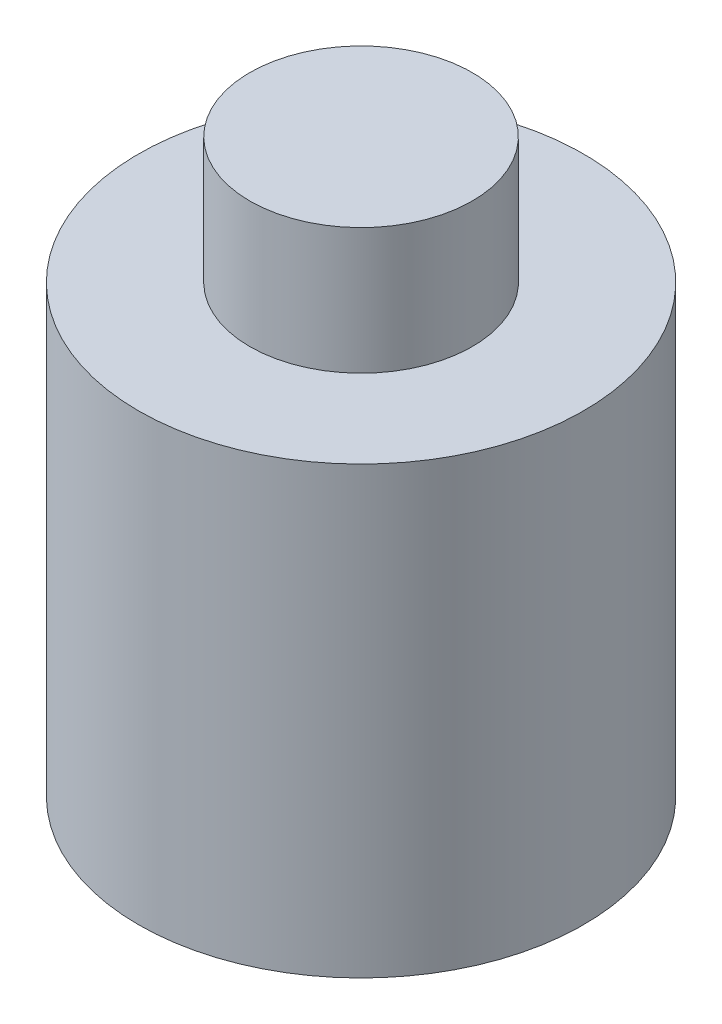
SolidWorks part; units mm, degrees
ref_plane "Front Plane" through (0, 0, 0) normal (0, 0, 1) x (1, 0, 0)
ref_plane "Top Plane" through (0, 0, 0) normal (0, 1, 0) x (1, 0, 0)
ref_plane "Right Plane" through (0, 0, 0) normal (1, 0, 0) x (0, 0, -1)
sketch "Sketch2" plane through (0, 0, 0) normal (0, 1, 0) x (1, 0, 0)
  circle A0 centre (0, 0) radius 3
  circle A1 centre (0, 0) radius 1
  dimension "D1" = 6
  dimension "D2" = 2
extrude "Boss-Extrude1" add sketch "Sketch2" along normal blind 6
sketch "Sketch3" plane through (0, 6, 0) normal (0, 1, 0) x (1, 0, 0)
  circle A2 centre (0, 0) radius 3 construction
  circle A3 centre (0, 0) radius 1.5
  dimension "D1" = 3
extrude "Boss-Extrude2" add sketch "Sketch3" along normal blind 1.7
